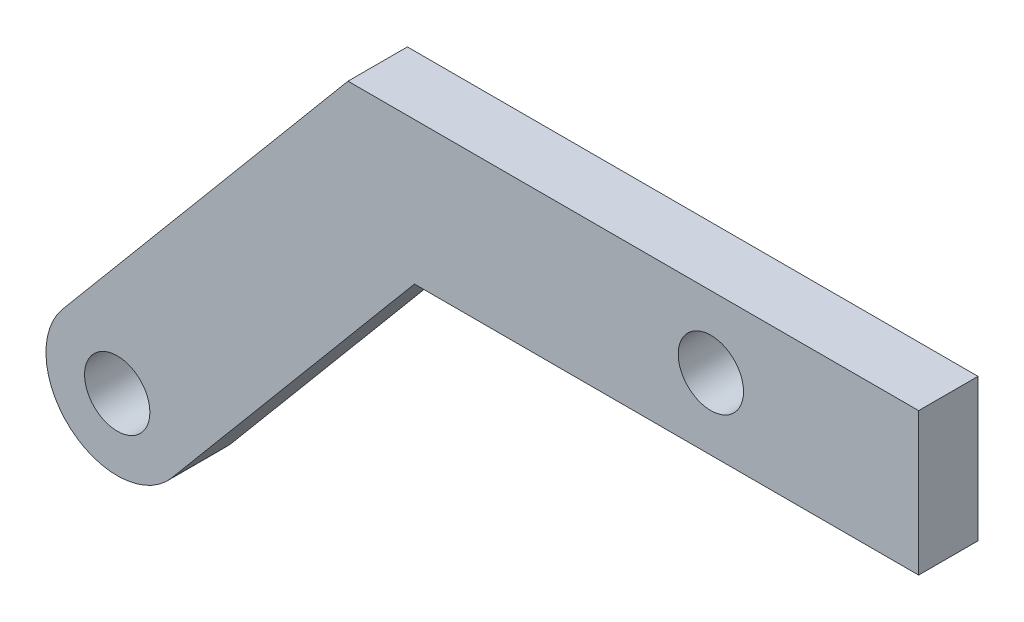
SolidWorks part; units mm, degrees
ref_plane "Front Plane" through (0, 0, 0) normal (0, 0, 1) x (1, 0, 0)
ref_plane "Top Plane" through (0, 0, 0) normal (0, 1, 0) x (1, 0, 0)
ref_plane "Right Plane" through (0, 0, 0) normal (1, 0, 0) x (0, 0, -1)
sketch "Sketch1" plane through (0, 0, 0) normal (0, 0, 1) x (1, 0, 0)
  line L0 (9.1925, -7.7135) -> (50.068, 41)
  line L1 (50.068, 41) -> (135, 41)
  line L2 (135, 41) -> (135, 65)
  line L3 (135, 65) -> (38.8766, 65)
  line L4 (38.8766, 65) -> (-9.1925, 7.7135)
  line L5 (55, 0) -> (-55, 0) construction
  arc A0 (-9.1925, 7.7135) -> (9.1925, -7.7135) centre (0, 0) ccw
  circle A1 centre (100, 53) radius 5.5
  circle A2 centre (0, 0) radius 5.5
  point P14 (135, 53)
  dimension "D1" = 24
  dimension "D5" = 11
  dimension "D6" = 11
  dimension "D2" = 50
  dimension "D3" = 65
  dimension "D4" = 24
  dimension "D7" = 135
  dimension "D8" = 35
extrude "Boss-Extrude1" add sketch "Sketch1" along normal blind 10
